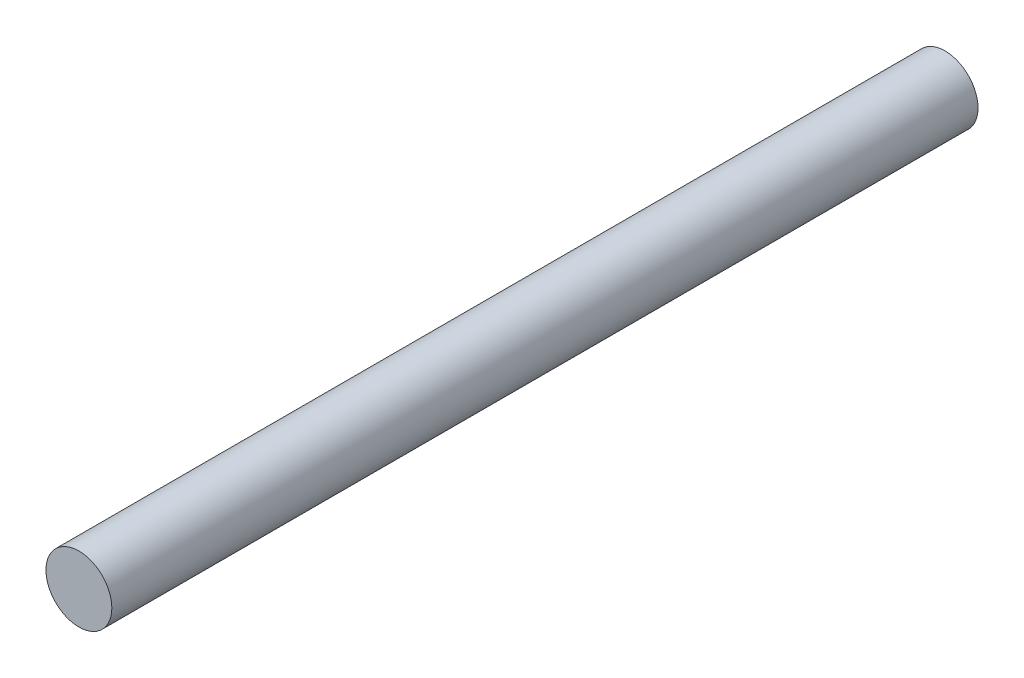
SolidWorks part; units mm, degrees
ref_plane "Plano frontal" through (0, 0, 0) normal (0, 0, 1) x (1, 0, 0)
ref_plane "Plano superior" through (0, 0, 0) normal (0, 1, 0) x (1, 0, 0)
ref_plane "Plano direito" through (0, 0, 0) normal (1, 0, 0) x (0, 0, -1)
sketch "Esboço1" plane through (0, 0, 0) normal (0, 0, 1) x (1, 0, 0)
  circle A0 centre (0, 0) radius 1.75
  dimension "D1" = 3.5
extrude "Ressalto-extrusão1" add sketch "Esboço1" along normal blind 46
